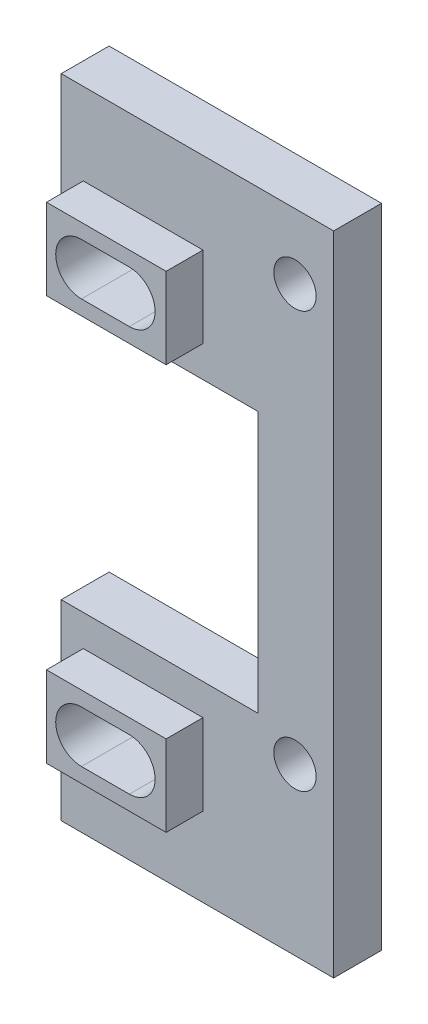
SolidWorks part; units mm, degrees
ref_plane "前视基准面" through (0, 0, 0) normal (0, 0, 1) x (1, 0, 0)
ref_plane "上视基准面" through (0, 0, 0) normal (0, 1, 0) x (1, 0, 0)
ref_plane "右视基准面" through (0, 0, 0) normal (1, 0, 0) x (0, 0, -1)
other "Configuration Table"
sketch "螺栓端底座，背面器件避空 profile" plane through (0, 0, 0) normal (0, 0, 1) x (1, 0, 0)
  line L0 (25.7, -32) -> (40.5, -32)
  line L1 (40.5, -32) -> (40.5, 3.15)
  line L2 (40.5, 3.15) -> (25.7, 3.15)
  line L3 (25.7, 3.15) -> (25.7, -7.4)
  line L4 (25.7, -7.4) -> (36.4, -7.4)
  line L5 (36.4, -7.4) -> (36.4, -21.6)
  line L6 (36.4, -21.6) -> (25.7, -21.6)
  line L7 (25.7, -21.6) -> (25.7, -32)
  line L8 (28.8, -26.9) -> (31.4, -26.9)
  line L9 (31.4, -24.1) -> (28.8, -24.1)
  line L10 (28.8, -4.9) -> (31.4, -4.9)
  line L11 (31.4, -2.1) -> (28.8, -2.1)
  circle A0 centre (38.4, -23) radius 1.15
  circle A1 centre (38.4, -0.4) radius 1.15
  arc A2 (31.4, -26.9) -> (31.4, -24.1) centre (31.4, -25.5) ccw
  arc A3 (28.8, -24.1) -> (28.8, -26.9) centre (28.8, -25.5) ccw
  arc A4 (31.4, -4.9) -> (31.4, -2.1) centre (31.4, -3.5) ccw
  arc A5 (28.8, -2.1) -> (28.8, -4.9) centre (28.8, -3.5) ccw
extrude "螺栓端底座，背面器件避空" add sketch "螺栓端底座，背面器件避空 profile" along normal blind 2.6
sketch "只托住开发板两端的边缘 profile" plane through (0, 0, 0) normal (0, 0, 1) x (1, 0, 0)
  line L0 (26.9, -27.7) -> (33.4, -27.7)
  line L1 (33.4, -27.7) -> (33.4, -23.3)
  line L2 (33.4, -23.3) -> (26.9, -23.3)
  line L3 (26.9, -23.3) -> (26.9, -27.7)
  line L4 (26.9, -5.7) -> (33.4, -5.7)
  line L5 (33.4, -5.7) -> (33.4, -1.3)
  line L6 (33.4, -1.3) -> (26.9, -1.3)
  line L7 (26.9, -1.3) -> (26.9, -5.7)
  line L8 (28.8, -26.9) -> (31.4, -26.9)
  line L9 (31.4, -24.1) -> (28.8, -24.1)
  line L10 (28.8, -4.9) -> (31.4, -4.9)
  line L11 (31.4, -2.1) -> (28.8, -2.1)
  arc A0 (31.4, -26.9) -> (31.4, -24.1) centre (31.4, -25.5) ccw
  arc A1 (28.8, -24.1) -> (28.8, -26.9) centre (28.8, -25.5) ccw
  arc A2 (31.4, -4.9) -> (31.4, -2.1) centre (31.4, -3.5) ccw
  arc A3 (28.8, -2.1) -> (28.8, -4.9) centre (28.8, -3.5) ccw
extrude "只托住开发板两端的边缘" add sketch "只托住开发板两端的边缘 profile" along normal blind 2 from offset 2.6
